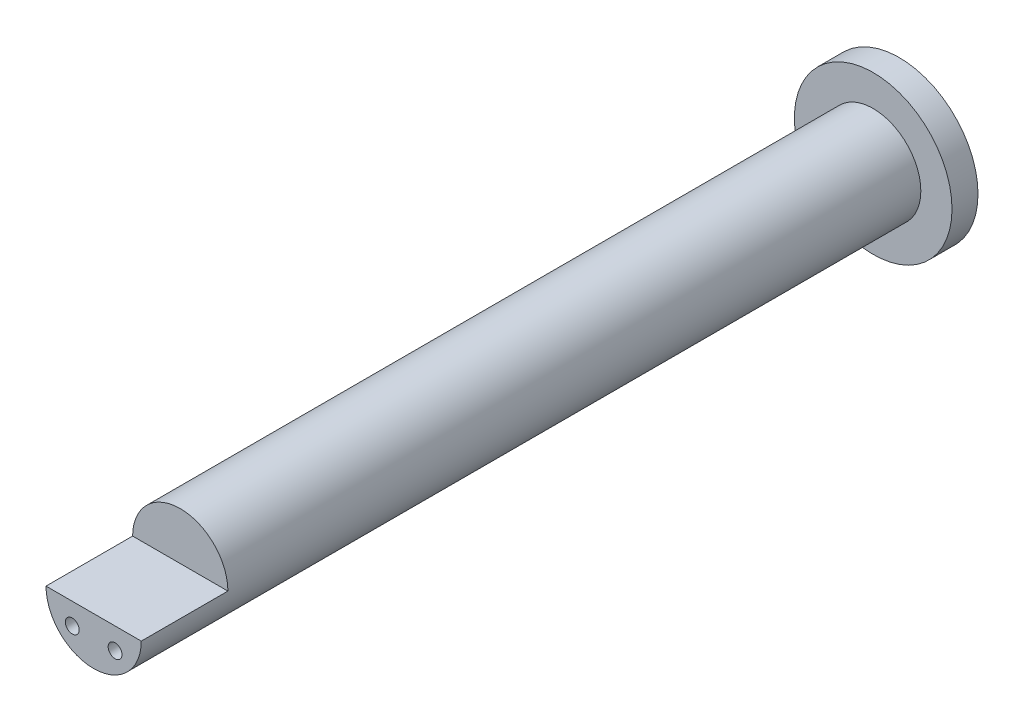
SolidWorks part; units mm, degrees
ref_plane "Plano frontal" through (0, 0, 0) normal (0, 0, 1) x (1, 0, 0)
ref_plane "Plano superior" through (0, 0, 0) normal (0, 1, 0) x (1, 0, 0)
ref_plane "Plano direito" through (0, 0, 0) normal (1, 0, 0) x (0, 0, -1)
sketch "Esboço1" plane through (0, 0, 0) normal (0, 0, 1) x (1, 0, 0)
  circle A0 centre (0, 0) radius 9.1
  dimension "D1" = 18.2
extrude "Ressalto-extrusão1" add sketch "Esboço1" along normal blind 3
sketch "Esboço2" plane through (0, 0, 3) normal (0, 0, 1) x (1, 0, 0)
  circle A0 centre (0, 0) radius 5.5
  dimension "D1" = 11
extrude "Ressalto-extrusão2" add sketch "Esboço2" along normal blind 80
sketch "Esboço3" plane through (0, 0, 83) normal (0, 0, 1) x (1, 0, 0)
  line L0 (-5.5, 0) -> (5.5, 0)
  circle A0 centre (0, 0) radius 5.5 construction
  circle A1 centre (0, 0) radius 5.5 construction
  arc A2 (-5.5, 0) -> (5.5, 0) centre (0, 0) ccw
extrude "Ressalto-extrusão3" add sketch "Esboço3" along normal blind 10
sketch "Esboço7" plane through (0, 0, 93) normal (0, 0, 1) x (1, 0, 0)
  line L1 (0, 0) -> (2.4749, -2.4749)
  line L2 (0, 0) -> (0, -9.9852) construction
  line L3 (5.5, 0) -> (-5.5, 0) construction
  line L4 (0, 0) -> (-2.4749, -2.4749)
  dimension "D1" = 3.5
  dimension "D2" = 45
hole_wizard "Furo roscado de M21" positions "Esboço8" profile "Esboço10" tap size "M2" standard "ISO"
sketch "Esboço8" plane through (0, 0, 93) normal (0, 0, 1) x (1, 0, 0)
  point P0 (-2.4749, -2.4749)
  point P3 (2.4749, -2.4749)
cosmetic thread "Rosca de furo3" parameters "D1"=10, "D2"=2
cosmetic thread "Rosca de furo4" parameters "D1"=10, "D2"=2
sketch "Esboço10" plane through (-2.4749, -2.4749, 93) normal (1, 0, 0) x (0, -1, 0)
  line L0 (0, 0) -> (0, 10.4807)
  line L1 (0, 10.4807) -> (0.8, 10)
  line L2 (0.8, 10) -> (0.8, 0)
  line L5 (0.8, 0) -> (0, 0)
  line L10 (0, 10.4807) -> (-0.8, 10) construction
  line L11 (0, -6.35) -> (0, 107.95) construction
  dimension "Tap Drill Dia." = 1.6
  dimension "Tap Drill Depth" = 10
  dimension "Drill Angle" = 118
